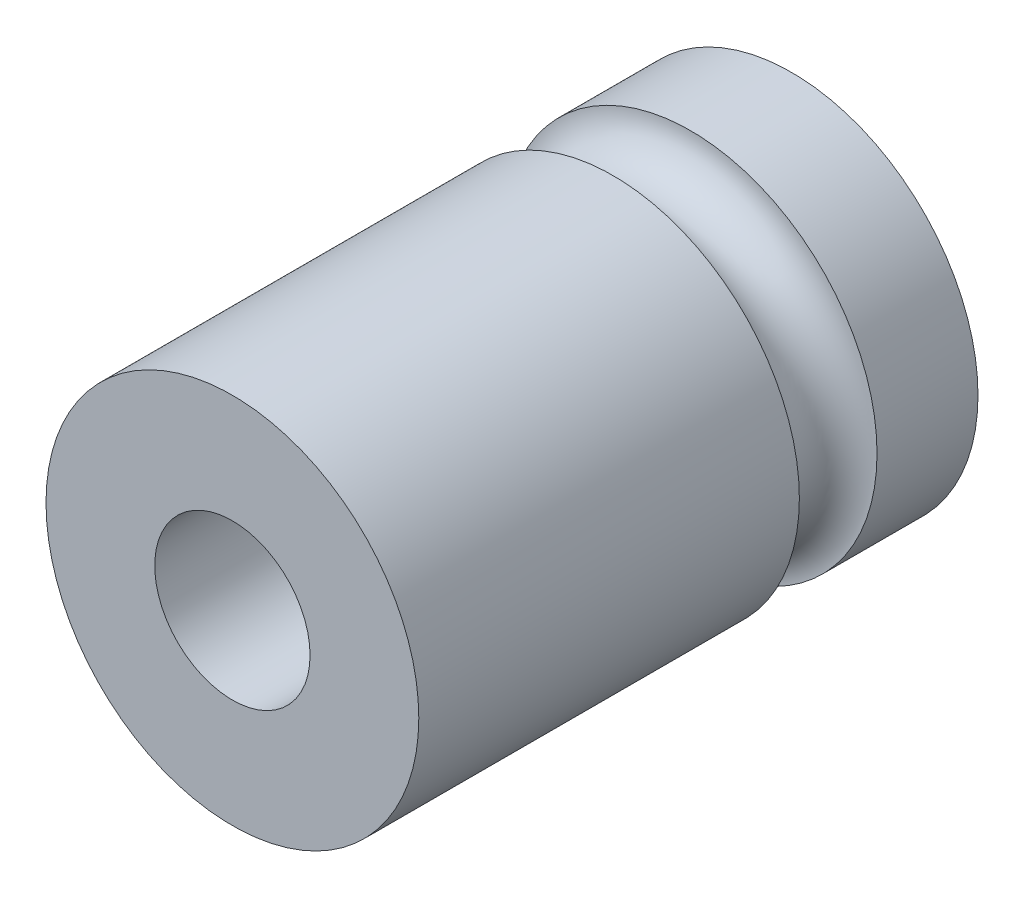
SolidWorks part; units mm, degrees
material "Custom Plastic"
ref_plane "Front Plane" through (0, 0, 0) normal (0, 0, 1) x (1, 0, 0)
ref_plane "Top Plane" through (0, 0, 0) normal (0, 1, 0) x (1, 0, 0)
ref_plane "Right Plane" through (0, 0, 0) normal (1, 0, 0) x (0, 0, -1)
sketch "Sketch1" plane through (0, 0, 0) normal (0, 0, 1) x (1, 0, 0)
  circle A0 centre (0, 0) radius 1.5875
  circle A1 centre (0, 0) radius 3.81
  dimension "D1" = 3.175
  dimension "D2" = 7.62
extrude "Boss-Extrude1" add sketch "Sketch1" along normal mid plane 11.43
sketch "Sketch2" plane through (0, 0, 0) normal (0, 1, 0) x (1, 0, 0)
  line L0 (3.81, -5.715) -> (3.81, 5.715) construction
  circle A0 centre (3.81, 2.8575) radius 0.7938
  dimension "D2" = 1.5875
  dimension "D1" = 2.8575
revolve "Cut-Revolve1" cut sketch "Sketch2" angle 360 about axis through (0, 0, 5.715) along (0, 0, -1)
